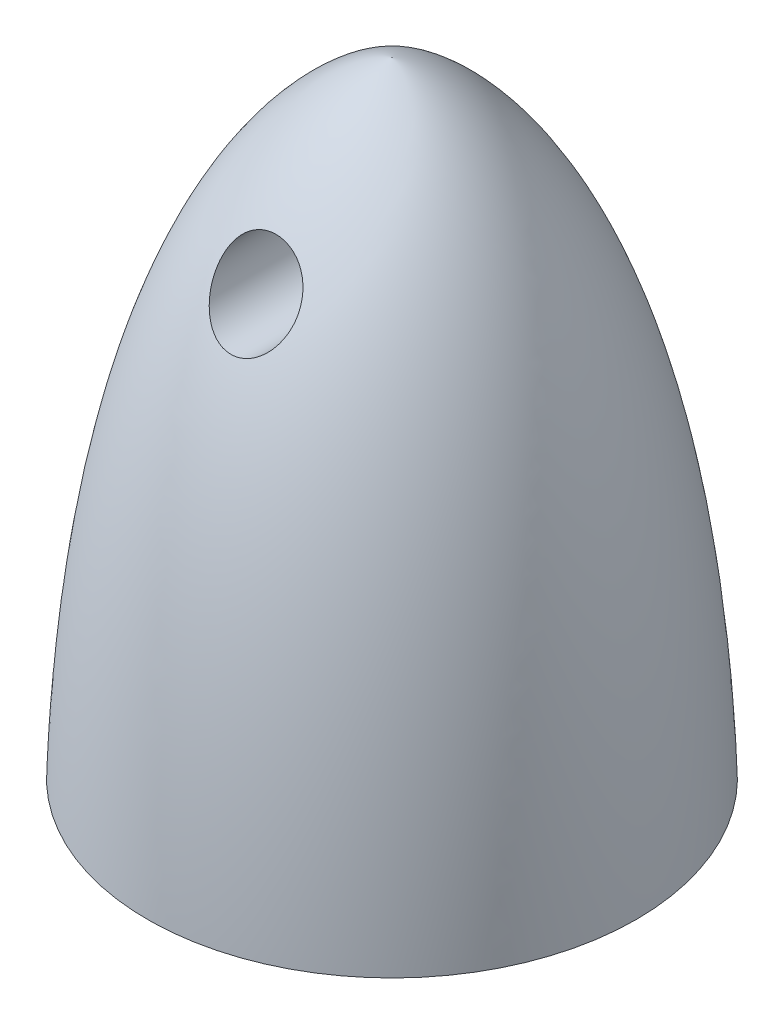
SolidWorks part; units mm, degrees
ref_plane "Front Plane" through (0, 0, 0) normal (0, 0, 1) x (1, 0, 0)
ref_plane "Top Plane" through (0, 0, 0) normal (0, 1, 0) x (1, 0, 0)
ref_plane "Right Plane" through (0, 0, 0) normal (1, 0, 0) x (0, 0, -1)
sketch "Sketch1" plane through (0, 0, 0) normal (0, 0, 1) x (1, 0, 0)
  line L0 (3.5, 3.5284) -> (3.5, 0)
  line L1 (3.5, 0) -> (9, 0)
  line L4 (0, 23) -> (0, 14)
  line L6 (3.5, 3.5284) -> (3.5, 14)
  line L7 (3.5, 14) -> (0, 14)
  line L8 (0, 0) -> (0, 11.9245) construction
  spline S0 degree 3 poles (0, 23) (0.0373, 22.984) (8.2621, 21.4802) (9, 0) knots 0 0 0 0 1 1 1 1
  dimension "D2" = 23
  dimension "D1" = 3.5
  dimension "5.5mm" = 5.5
  dimension "D3" = 14
revolve "Revolve1" add sketch "Sketch1" angle 360 about L8
sketch "Sketch2" plane through (0, 0, 0) normal (0, 1, 0) x (1, 0, 0)
  line L1 (5.6292, 0) -> (2.8146, 4.875)
  line L2 (2.8146, 4.875) -> (-2.8146, 4.875)
  line L3 (-2.8146, 4.875) -> (-5.6292, 0)
  line L4 (-5.6292, 0) -> (-2.8146, -4.875)
  line L5 (-2.8146, -4.875) -> (2.8146, -4.875)
  line L6 (2.8146, -4.875) -> (5.6292, 0)
  circle A0 centre (0, 0) radius 4.875 construction
  dimension "D1" = 9.75
extrude "Cut-Extrude1" cut sketch "Sketch2" along normal blind 7
sketch "Sketch4" plane through (0, 0, 0) normal (0, 0, 1) x (1, 0, 0)
  circle A0 centre (0, 18) radius 1.5
  dimension "D1" = 3
  dimension "D2" = 5
extrude "Cut-Extrude2" cut sketch "Sketch4" against normal mid plane 17
chamfer "Chamfer1" distance 0.5 angle 45 6 edges at (-4.2219, 0, 2.4375) (-4.2219, 0, -2.4375) (0, 0, -4.875) (0, 0, 4.875) (4.2219, 0, 2.4375) (4.2219, 0, -2.4375)
fillet "Fillet1" radius 0.5 2 edges at (0, 7, 3.5) (3.5, 14, 0)
